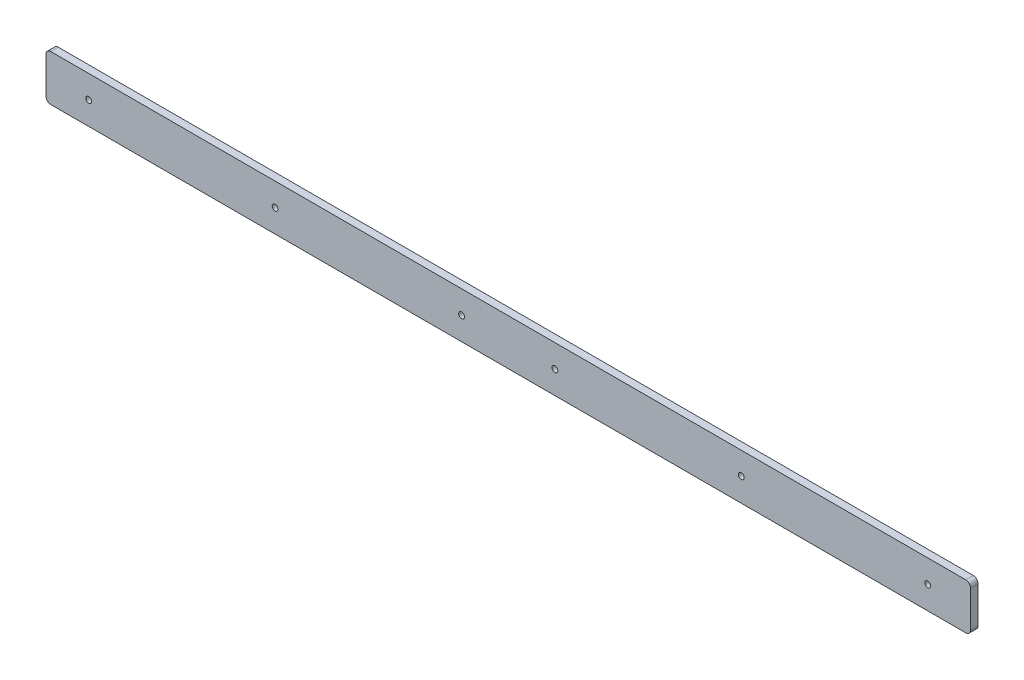
SolidWorks part; units mm, degrees
material "1100-H12 Rod (SS)"
ref_plane "X-Y Datum" through (0, 0, 0) normal (0, 0, 1) x (1, 0, 0)
ref_plane "X-Z Datum" through (0, 0, 0) normal (0, 1, 0) x (1, 0, 0)
ref_plane "Y-Z Datum" through (0, 0, 0) normal (1, 0, 0) x (0, 0, -1)
sketch "Sketch1" plane through (0, 0, 0) normal (0, 0, 1) x (1, 0, 0)
  line L1 (0, 0) -> (196.4572, 0)
  line L2 (0, 0) -> (0, 9.7577)
  line L3 (0, 9.7577) -> (196.4572, 9.7577)
  line L4 (196.4572, 0) -> (196.4572, 9.7577)
extrude "Boss-Extrude1" add sketch "Sketch1" along normal blind 1.6002 contours L3 L4 L1 L2
sketch "Sketch2" plane through (0, 0, 1.6002) normal (0, 0, 1) x (1, 0, 0)
  line L0 (0, 4.8788) -> (9.075, 4.8788) construction
  line L1 (0, 0) -> (0, 9.7577) construction
  line L2 (9.075, 4.8788) -> (48.699, 4.8788) construction
  line L3 (196.4572, 0) -> (196.4572, 9.7577) construction
  circle A0 centre (9.075, 4.8788) radius 0.625
  circle A1 centre (48.699, 4.8788) radius 0.625
  circle A2 centre (88.323, 4.8788) radius 0.625
  circle A3 centre (187.3822, 4.8788) radius 0.625
  circle A4 centre (147.7582, 5.0025) radius 0.625
  circle A5 centre (108.1342, 4.8788) radius 0.625
  dimension "D1" = 39.624
  dimension "D2" = 39.624
  dimension "D3" = 9.075
  dimension "D4" = 39.624
  dimension "D5" = 39.624
extrude "Cut-Extrude1" cut sketch "Sketch2" against normal through all
fillet "Fillet1" radius 1 4 edges at (196.4572, 0, 0.8001) (196.4572, 9.7577, 0.8001) (0, 0, 0.8001) (0, 9.7577, 0.8001)
